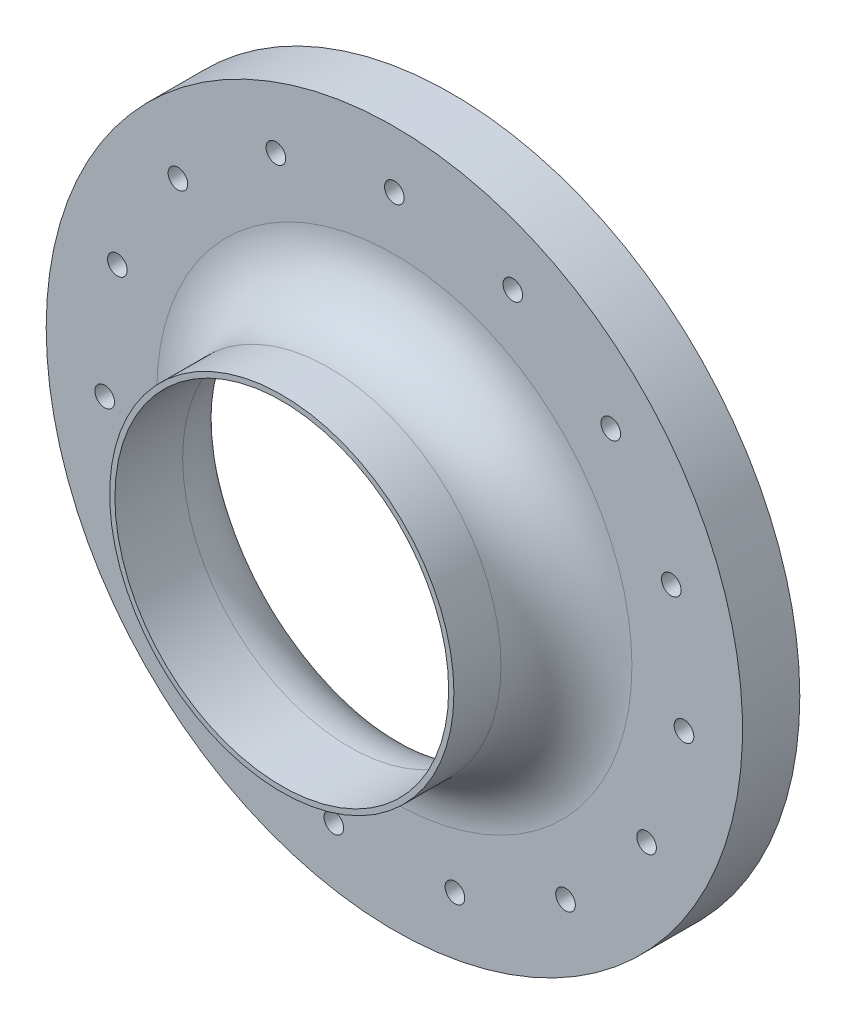
SolidWorks part; units mm, degrees
ref_plane "Plan1" through (0, 0, 0) normal (0, 0, 1) x (1, 0, 0)
ref_plane "Plan2" through (0, 0, 0) normal (0, 1, 0) x (1, 0, 0)
ref_plane "Plan3" through (0, 0, 0) normal (1, 0, 0) x (0, 0, -1)
sketch "Esquisse1" plane through (0, 0, 0) normal (1, 0, 0) x (0, 0, -1)
  line L0 (0, 0) -> (105.4524, 0) construction
  line L3 (0, 25.5) -> (0, 26.3)
  line L4 (0, 26.3) -> (7.2, 26.3)
  line L5 (17.2, 36.3) -> (17.2, 56)
  line L6 (17.2, 56) -> (22, 56)
  line L7 (22, 56) -> (22, 57.15)
  line L8 (22, 57.15) -> (32.8, 57.15)
  line L9 (32.8, 57.15) -> (32.8, 54.6)
  line L10 (32.8, 54.6) -> (27.8, 54.6)
  line L11 (27.8, 54.6) -> (27.8, 53.45)
  line L12 (20.85, 46.5) -> (20.85, 36)
  line L13 (1.5, 25.5) -> (-21.1015, 25.5) construction
  line L14 (1.5, 25.5) -> (10.35, 25.5)
  line L15 (1.5, 25.5) -> (0, 25.5)
  arc A0 (7.2, 26.3) -> (17.2, 36.3) centre (7.2, 36.3) ccw
  arc A1 (27.8, 53.45) -> (20.85, 46.5) centre (27.8, 46.5) ccw
  arc A2 (10.35, 25.5) -> (20.85, 36) centre (10.35, 36) ccw
  dimension "D15" = 72
  dimension "D16" = 3.6643
  dimension "D2" = 7.2
  dimension "D3" = 52.6
  dimension "D5" = 51
  dimension "D6" = 114.3
  dimension "D7" = 112
  dimension "D8" = 32.8
  dimension "D9" = 4.8
  dimension "D10" = 10.8
  dimension "D11" = 109.2
  dimension "D12" = 5
  dimension "D13" = 106.9
  dimension "D14" = 93
  dimension "D17" = 8.85
revolve "Base-Révolution" add sketch "Esquisse1" angle 360 about L0
sketch "Esquisse2" plane through (0, 0, -17.2) normal (0, 0, 1) x (1, 0, 0)
  line L0 (0, 0) -> (0, 44.5) construction
  circle A0 centre (0, 44.5) radius 1.5
  circle A1 centre (18.0998, 40.6528) radius 1.5
  circle A2 centre (33.0699, 29.7763) radius 1.5
  circle A3 centre (42.322, 13.7513) radius 1.5
  circle A4 centre (44.2562, -4.6515) radius 1.5
  circle A5 centre (38.5381, -22.25) radius 1.5
  circle A6 centre (26.1564, -36.0013) radius 1.5
  circle A7 centre (9.2521, -43.5276) radius 1.5
  circle A8 centre (-9.2521, -43.5276) radius 1.5
  circle A9 centre (-26.1564, -36.0013) radius 1.5
  circle A10 centre (-38.5381, -22.25) radius 1.5
  circle A11 centre (-44.2562, -4.6515) radius 1.5
  circle A12 centre (-42.322, 13.7513) radius 1.5
  circle A13 centre (-33.0699, 29.7763) radius 1.5
  circle A14 centre (-18.0998, 40.6528) radius 1.5
  dimension "D1" = 3
  dimension "D2" = 44.5
  dimension "D3" = 44.5
extrude "Enlèv. mat.-Extru.1" cut sketch "Esquisse2" against normal through all
ref_plane "Plan4" through (0, 57.5, 0) normal (0, 1, 0) x (-1, 0, 0)
sketch "Esquisse3" plane through (0, 57.5, 0) normal (0, 1, 0) x (-1, 0, 0)
  line L0 (0, -20.85) -> (0, -17.2) construction
  line L1 (56, -17.2) -> (-56, -17.2) construction
  circle A0 centre (0, -19.5) radius 1
  dimension "D1" = 2
  dimension "D2" = 2.3
extrude "Enlèv. mat.-Extru.2" cut sketch "Esquisse3" against normal blind 3
pattern_circular "Répétition circulaire1" count 4 over 360 about axis through (0, 0, 0) along (0, 0, 1) of "Enlèv. mat.-Extru.2"
sketch "Sketch1" plane through (0, 0, -32.8) normal (0, 0, -1) x (-1, 0, 0)
  circle A0 centre (0, 0) radius 57.15
  circle A1 centre (0, 0) radius 53.2
  dimension "D1" = 106.4
extrude "Cut-Extrude1" cut sketch "Sketch1" against normal through all
